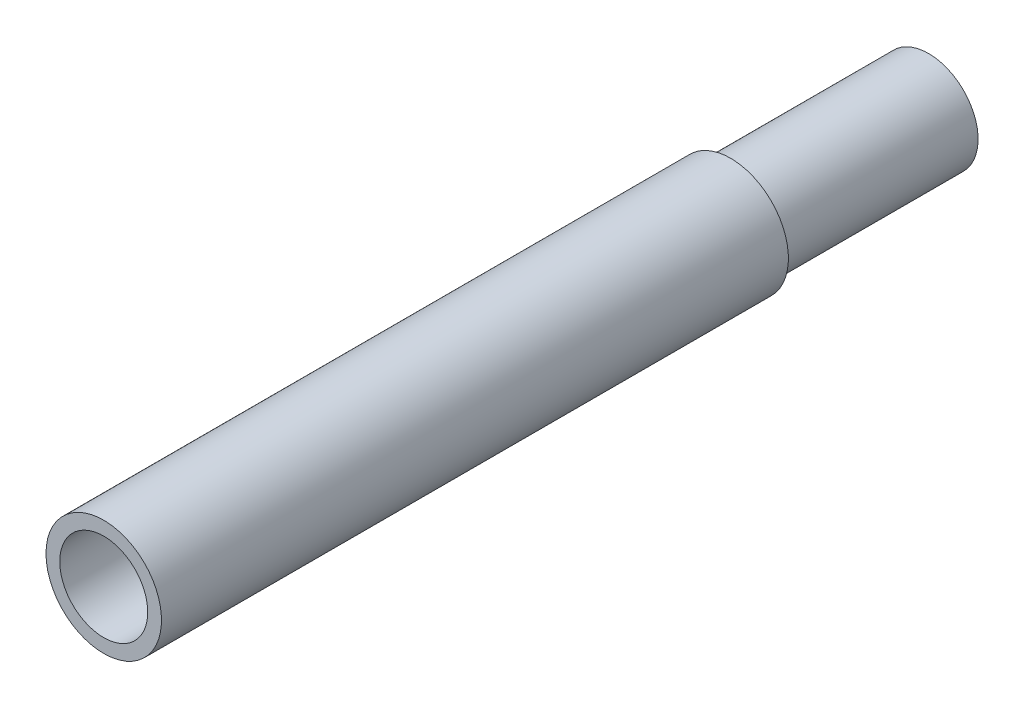
SolidWorks part; units mm, degrees
ref_plane "Front Plane" through (0, 0, 0) normal (0, 0, 1) x (1, 0, 0)
ref_plane "Top Plane" through (0, 0, 0) normal (0, 1, 0) x (1, 0, 0)
ref_plane "Right Plane" through (0, 0, 0) normal (1, 0, 0) x (0, 0, -1)
sketch "Sketch2" plane through (0, 0, 0) normal (0, 0, 1) x (1, 0, 0)
  circle A0 centre (0, 0) radius 8
  circle A1 centre (0, 0) radius 10.5
  dimension "D1" = 16
  dimension "D2" = 21
extrude "Boss-Extrude1" add sketch "Sketch2" along normal blind 114
sketch "Sketch4" plane through (0, 0, 0) normal (0, 0, -1) x (-1, 0, 0)
  circle A0 centre (0, 0) radius 8
  circle A1 centre (0, 0) radius 9
  dimension "D1" = 16
  dimension "D2" = 18
extrude "Boss-Extrude2" add sketch "Sketch4" along normal blind 36
fillet "Fillet2" [suppressed] radius 1
fillet "Fillet3" [suppressed] radius 1.75
